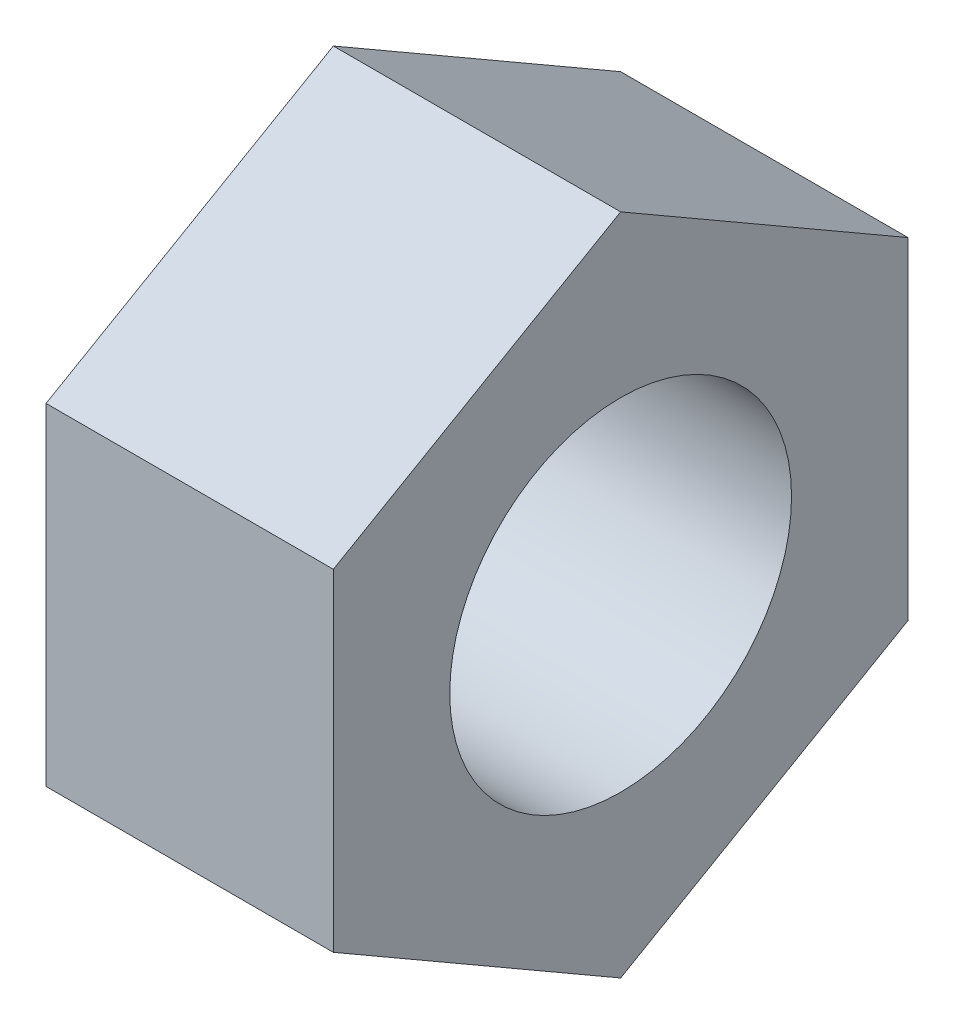
SolidWorks part; units mm, degrees
material "Free-Cutting Brass, UNS C36000"
ref_plane "Front Plane" through (0, 0, 0) normal (0, 0, 1) x (1, 0, 0)
ref_plane "Top Plane" through (0, 0, 0) normal (0, 1, 0) x (1, 0, 0)
ref_plane "Right Plane" through (0, 0, 0) normal (1, 0, 0) x (0, 0, -1)
sketch "Sketch1" plane through (0, 0, 0) normal (1, 0, 0) x (0, 0, -1)
  line L0 (0, 1.65) -> (0, -1.65) construction
  line L1 (5.3375, -3.0816) -> (5.3375, 3.0816)
  line L2 (5.3375, 3.0816) -> (0, 6.1632)
  line L3 (0, 6.1632) -> (-5.3375, 3.0816)
  line L4 (-5.3375, 3.0816) -> (-5.3375, -3.0816)
  line L5 (-5.3375, -3.0816) -> (0, -6.1632)
  line L6 (0, -6.1632) -> (5.3375, -3.0816)
  circle A0 centre (0, 0) radius 5.3375 construction
  dimension "Hex_Head_Size" = 10.675
extrude "Hex_Head" add sketch "Sketch1" along normal blind 5.3375
sketch "Sketch2" plane through (0, 0, 0) normal (-1, 0, 0) x (0, 0, 1)
  circle A0 centre (0, 0) radius 3.175
  dimension "Thread_ID" = 6.35
extrude "Cut-Extrude1" cut sketch "Sketch2" against normal through all
